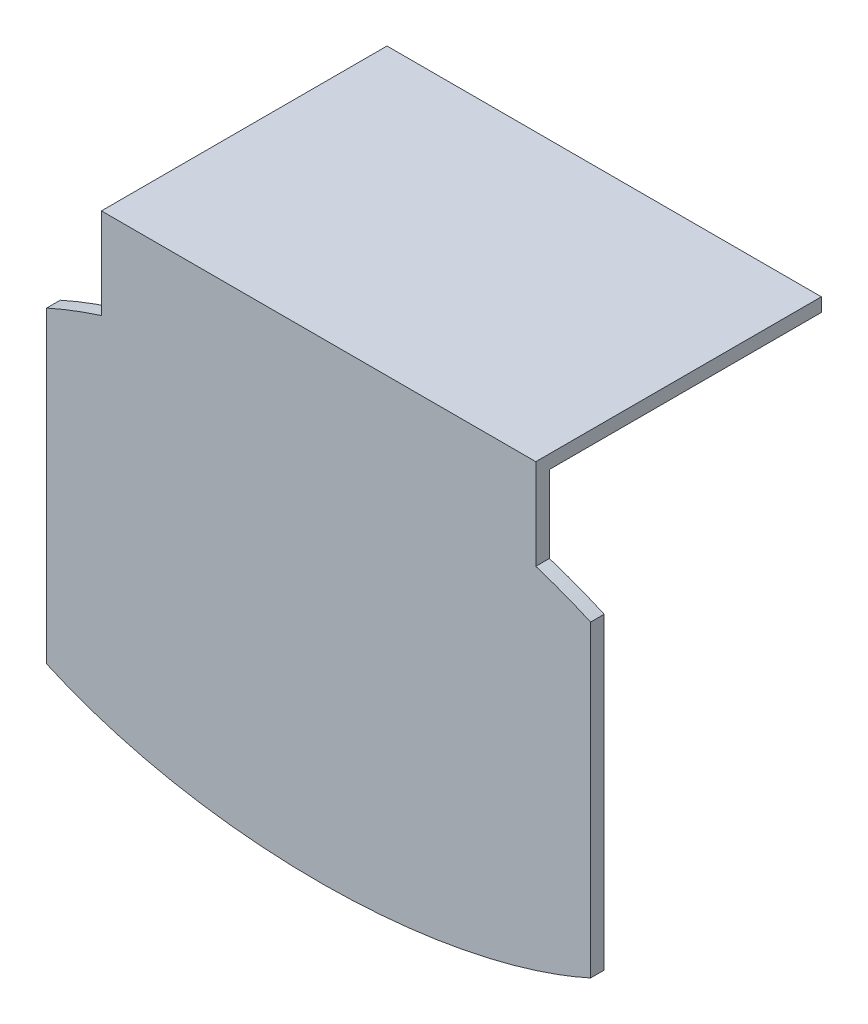
SolidWorks part; units mm, degrees
ref_plane "前视基准面" through (0, 0, 0) normal (0, 0, 1) x (1, 0, 0)
ref_plane "上视基准面" through (0, 0, 0) normal (0, 1, 0) x (1, 0, 0)
ref_plane "右视基准面" through (0, 0, 0) normal (1, 0, 0) x (0, 0, -1)
sketch "草图1" plane through (0, 0, 0) normal (0, 0, 1) x (1, 0, 0)
  line L0 (-60, 34) -> (-60, -34)
  line L1 (60, 34) -> (60, -34)
  ellipse E0 centre (0, 0) end of major axis (-90.0291, 0) minor radius 45.604 (-60, -34) -> (60, -34) ccw
  ellipse E1 centre (0, 0) end of major axis (-90.0291, 0) minor radius 45.604 (60, 34) -> (-60, 34) ccw
  point P10 (-60, -34)
  point P12 (-60, 42.9076)
  point P13 (-60, -42.9076)
  point P15 (-60, 34)
  dimension "D1" = 60
  dimension "D2" = 60
extrude "凸台-拉伸1" add sketch "草图1" along normal blind 3
sketch "草图7" plane through (0, 0, 0) normal (0, 0, -1) x (-1, 0, 0)
  line L2 (-0.0475, 38.6089) -> (-47.9144, 38.6089)
  line L3 (-0.0475, 38.6089) -> (47.9144, 38.6089)
  ellipse E1 centre (0, 0) end of major axis (90.0291, 0) minor radius 45.604 (60, 34) -> (-60, 34) ccw construction
extrude "切除-拉伸10" cut sketch "草图7" against normal blind 3 and the other way through all
sketch "草图9" plane through (0, 38.6089, 0) normal (0, 1, 0) x (1, 0, 0)
  line L0 (-47.9144, 0) -> (-47.9144, -3)
  line L1 (-47.9144, -3) -> (47.9144, -3)
  line L2 (47.9144, -3) -> (47.9144, 0)
  line L3 (47.9144, 0) -> (-47.9144, 0)
extrude "凸台-拉伸2" add sketch "草图9" along normal blind 20
sketch "草图10" plane through (0, 0, 0) normal (0, 0, -1) x (-1, 0, 0)
  line L0 (-47.9144, 58.6089) -> (47.9144, 58.6089)
  line L1 (47.9144, 58.6089) -> (47.9144, 55.6089)
  line L2 (47.9144, 58.6089) -> (47.9144, 38.6089) construction
  line L3 (47.9144, 55.6089) -> (-47.9144, 55.6089)
  line L4 (-47.9144, 58.6089) -> (-47.9144, 38.6089) construction
  line L5 (-47.9144, 55.6089) -> (-47.9144, 58.6089)
extrude "凸台-拉伸3" add sketch "草图10" along normal blind 60
